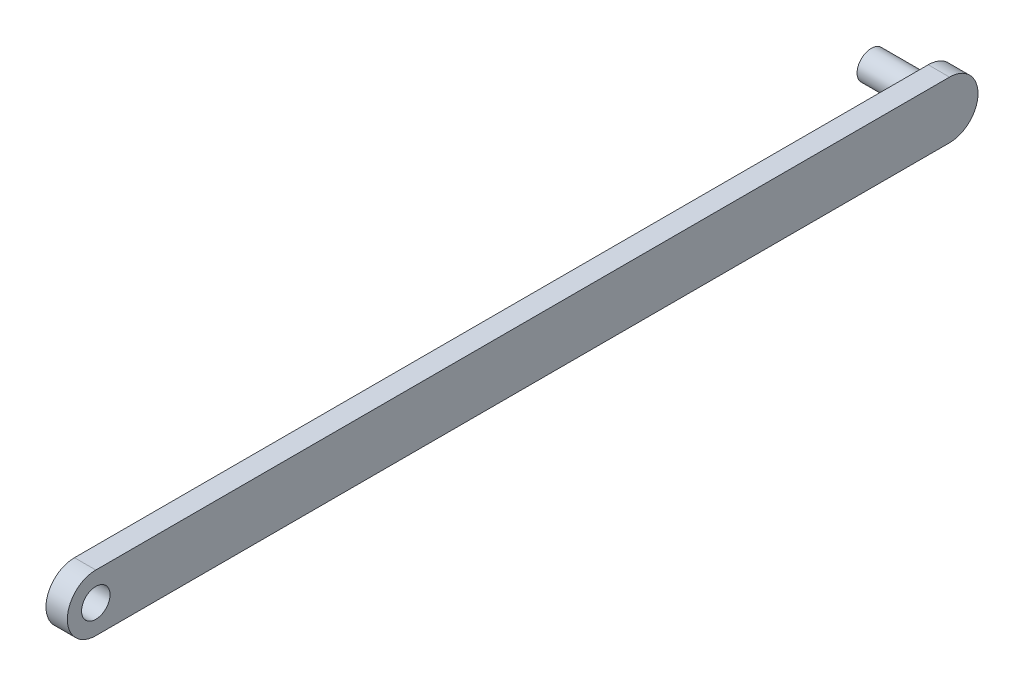
SolidWorks part; units mm, degrees
ref_plane "Front Plane" through (0, 0, 0) normal (0, 0, 1) x (1, 0, 0)
ref_plane "Top Plane" through (0, 0, 0) normal (0, 1, 0) x (1, 0, 0)
ref_plane "Right Plane" through (0, 0, 0) normal (1, 0, 0) x (0, 0, -1)
sketch "Sketch2" plane through (0, 0, 0) normal (1, 0, 0) x (0, 0, -1)
  line L0 (0, 0) -> (381, 0) construction
  line L1 (0, 12.7) -> (381, 12.7)
  line L2 (0, -12.7) -> (381, -12.7)
  circle A0 centre (0, 0) radius 6.35
  arc A1 (0, 12.7) -> (0, -12.7) centre (0, 0) ccw
  arc A2 (381, -12.7) -> (381, 12.7) centre (381, 0) ccw
  point P3 (190.5, 0)
  dimension "D1" = 12.7
  dimension "D3" = 12.7
  dimension "D2" = 381
extrude "Boss-Extrude1" add sketch "Sketch2" along normal blind 9.525
sketch "Sketch4" plane through (0, 0, 0) normal (-1, 0, 0) x (0, 0, 1)
  line L0 (0, 0) -> (-381, 0) construction
  circle A0 centre (-381, 0) radius 6.35
  dimension "D2" = 12.7
  dimension "D1" = 381
extrude "Boss-Extrude3" add sketch "Sketch4" along normal blind 25.4
